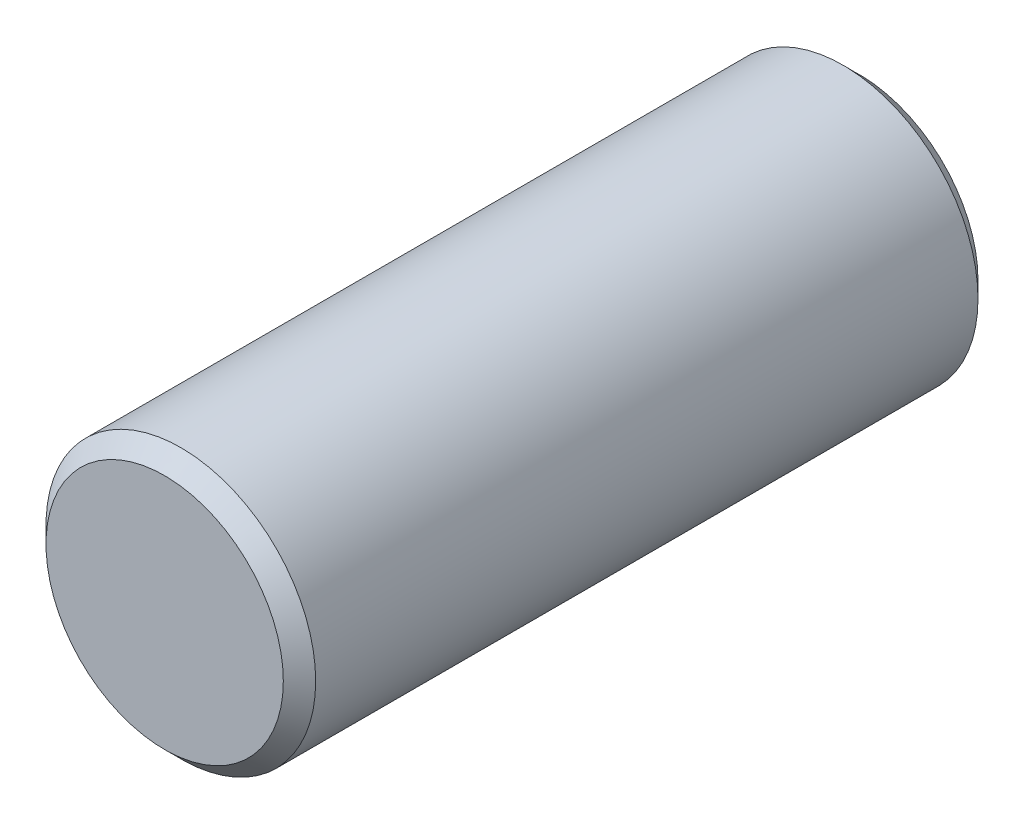
SolidWorks part; units mm, degrees
material "Cast Stainless Steel"
ref_plane "Front" through (0, 0, 0) normal (0, 0, 1) x (1, 0, 0)
ref_plane "Top" through (0, 0, 0) normal (0, 1, 0) x (1, 0, 0)
ref_plane "Right" through (0, 0, 0) normal (1, 0, 0) x (0, 0, -1)
sketch "Sketch2" plane through (0, 0, 0) normal (0, 0, 1) x (1, 0, 0)
  circle A0 centre (0, 0) radius 3.175
  dimension "D1" = 6.35
extrude "Extrude1" add sketch "Sketch2" along normal mid plane 16.3576
chamfer "Chamfer1" distance 0.381 angle 45 2 edges at (3.175, 0, 8.1788) (3.175, 0, -8.1788)
